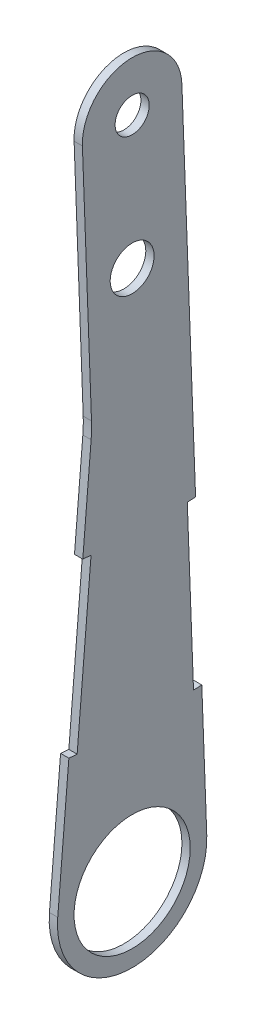
SolidWorks part; units mm, degrees
material "AISI 4130 Steel, annealed at 865C"
ref_plane "X-Y Datum" through (0, 0, 0) normal (0, 0, 1) x (1, 0, 0)
ref_plane "X-Z Datum" through (0, 0, 0) normal (0, 1, 0) x (1, 0, 0)
ref_plane "Y-Z Datum" through (0, 0, 0) normal (1, 0, 0) x (0, 0, -1)
sketch "Sketch1" plane through (0, 0, 0) normal (1, 0, 0) x (0, 0, -1)
  line L0 (0, 0) -> (0, 101.6) construction
  line L1 (0, 0) -> (0, 127) construction
  line L3 (9.5183, 127.3572) -> (12.1343, 57.6456)
  line L6 (-12.1073, 26.5086) -> (-10.5254, 26.3755)
  line L7 (-9.4449, 58.1468) -> (-7.863, 58.0137)
  line L8 (-10.5254, 26.3755) -> (-7.863, 58.0137)
  line L9 (13.325, 25.9179) -> (14.2775, 0.5358)
  line L10 (-12.1073, 26.5086) -> (-14.2372, 1.1981)
  line L15 (-9.5183, 126.6428) -> (-7.7759, 80.2121)
  line L16 (-9.4449, 58.1468) -> (-7.8475, 77.1297)
  line L17 (11.7386, 25.8584) -> (10.5479, 57.5861)
  line L18 (11.7386, 25.8584) -> (13.325, 25.9179)
  line L19 (10.5479, 57.5861) -> (12.1343, 57.6456)
  arc A0 (-14.2372, 1.1981) -> (14.2775, 0.5358) centre (0, 0) ccw
  arc A2 (-9.5183, 126.6428) -> (9.5183, 127.3572) centre (0, 127) cw
  circle A3 centre (0, 0) radius 11.1125
  arc A4 (-7.8475, 77.1297) -> (-7.7759, 80.2121) centre (-33.1581, 79.2596) ccw
  circle A5 centre (0, 0) radius 14.2875 construction
  point P14 (21.1318, 6.4606)
  dimension "D2" = 9.525
  dimension "D7" = 25.4
  dimension "D8" = 19.05
  dimension "D5" = 22.225
  dimension "D3" = 1.5875
  dimension "D4" = 31.75
  dimension "D6" = 25.4
  dimension "D1" = 3.175
extrude "Boss-Extrude1" add sketch "Sketch1" along normal blind 1.5875
hole_wizard "1/4 Clearance Hole1" positions "Sketch2" profile "Sketch3" hole size "1/4" standard "ANSI Inch" end condition through all
sketch "Sketch2" plane through (1.5875, 0, 0) normal (1, 0, 0) x (0, 0, -1)
  point P2 (0, 127)
sketch "Sketch3" plane through (1.5875, 127, 0) normal (0, 1, 0) x (0, 0, -1)
  line L0 (0, 0) -> (0, 1.5875)
  line L1 (0, 1.5875) -> (3.2639, 1.5875)
  line L2 (3.2639, 1.5875) -> (3.2639, 0)
  line L5 (3.2639, 0) -> (0, 0)
  line L11 (0, -6.35) -> (0, 107.95) construction
  dimension "Thru Hole Dia." = 6.5278
  dimension "Thru Hole Depth" = 1.5875
hole_wizard "M8 Clearance Hole1" positions "Sketch4" profile "Sketch5" hole size "M8" standard "ANSI Metric" end condition through all
sketch "Sketch4" plane through (1.5875, 0, 0) normal (1, 0, 0) x (0, 0, -1)
  point P0 (0, 101.6)
sketch "Sketch5" plane through (1.5875, 101.6, 0) normal (0, 1, 0) x (0, 0, -1)
  line L0 (0, 0) -> (0, 1.5875)
  line L1 (0, 1.5875) -> (4.2, 1.5875)
  line L2 (4.2, 1.5875) -> (4.2, 0)
  line L5 (4.2, 0) -> (0, 0)
  line L11 (0, -6.35) -> (0, 107.95) construction
  dimension "Thru Hole Dia." = 8.4
  dimension "Thru Hole Depth" = 1.5875
